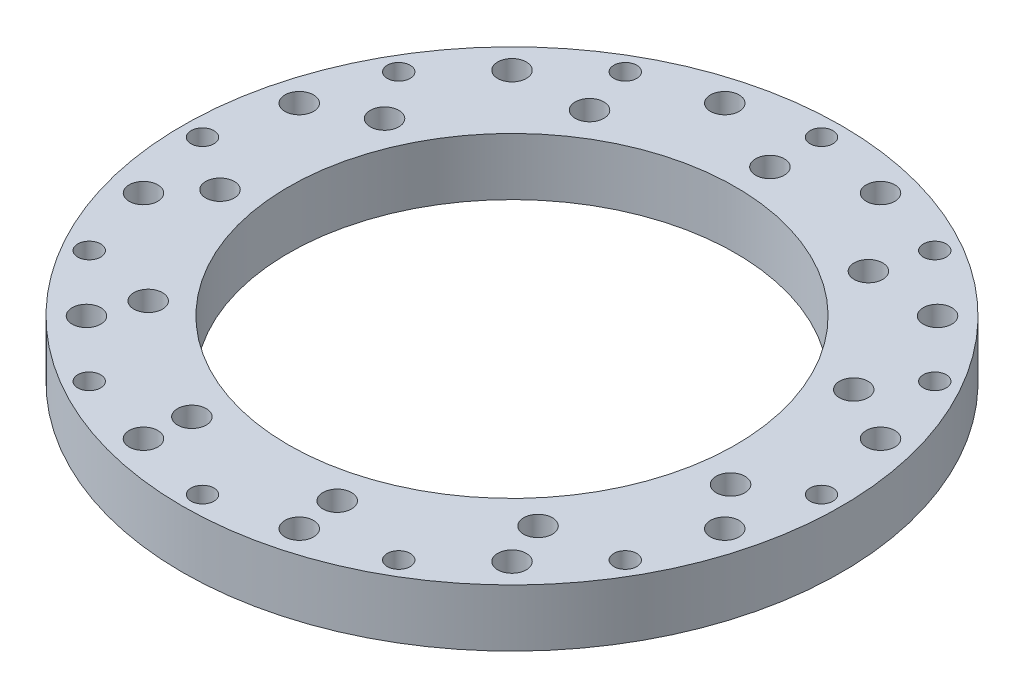
SolidWorks part; units mm, degrees
ref_plane "Front Plane" through (0, 0, 0) normal (0, 0, 1) x (1, 0, 0)
ref_plane "Top Plane" through (0, 0, 0) normal (0, 1, 0) x (1, 0, 0)
ref_plane "Right Plane" through (0, 0, 0) normal (1, 0, 0) x (0, 0, -1)
sketch "Sketch1" plane through (0, 0, 0) normal (0, 1, 0) x (1, 0, 0)
  line L0 (0, 0) -> (0, 52.5) construction
  line L1 (0, 0) -> (13.588, 50.7111) construction
  circle A12 centre (0, 0) radius 39
  circle A13 centre (0, 0) radius 57.5
  circle A14 centre (0, 0) radius 54 construction
  circle A15 centre (0, 54) radius 2
  circle A16 centre (27, 46.7654) radius 2
  circle A17 centre (46.7654, 27) radius 2
  circle A18 centre (54, 0) radius 2
  circle A19 centre (46.7654, -27) radius 2
  circle A20 centre (27, -46.7654) radius 2
  circle A21 centre (0, -54) radius 2
  circle A22 centre (-27, -46.7654) radius 2
  circle A23 centre (-46.7654, -27) radius 2
  circle A24 centre (-54, 0) radius 2
  circle A25 centre (-46.7654, 27) radius 2
  circle A26 centre (-27, 46.7654) radius 2
  circle A27 centre (0, 0) radius 52.5 construction
  circle A34 centre (13.588, 50.7111) radius 2.5
  circle A35 centre (37.1231, 37.1231) radius 2.5
  circle A36 centre (50.7111, 13.588) radius 2.5
  circle A37 centre (50.7111, -13.588) radius 2.5
  circle A38 centre (37.1231, -37.1231) radius 2.5
  circle A39 centre (13.588, -50.7111) radius 2.5
  circle A40 centre (-13.588, -50.7111) radius 2.5
  circle A41 centre (-37.1231, -37.1231) radius 2.5
  circle A42 centre (-50.7111, -13.588) radius 2.5
  circle A43 centre (-50.7111, 13.588) radius 2.5
  circle A44 centre (-37.1231, 37.1231) radius 2.5
  circle A45 centre (-13.588, 50.7111) radius 2.5
  point P21 (0, 0)
  point P28 (0, 0)
  point P56 (0, 0)
  point P60 (0, 0)
  dimension "D1" = 105
  dimension "D2" = 15
  dimension "D4" = 115
  dimension "D5" = 78
  dimension "D6" = 108
  dimension "D7" = 4
  dimension "D3" = 5
  dimension "D8" = 12
extrude "Boss-Extrude1" add sketch "Sketch1" along normal blind 10
sketch "Sketch2" plane through (0, 10, 0) normal (0, 1, 0) x (1, 0, 0)
  circle A0 centre (0, 0) radius 45 construction
  circle A1 centre (0, 45) radius 2.5
  circle A2 centre (24.3288, 37.8564) radius 2.5
  circle A3 centre (40.9334, 18.6937) radius 2.5
  circle A4 centre (44.542, -6.4042) radius 2.5
  circle A5 centre (34.0087, -29.4687) radius 2.5
  circle A6 centre (12.678, -43.1772) radius 2.5
  circle A7 centre (-12.678, -43.1772) radius 2.5
  circle A8 centre (-34.0087, -29.4687) radius 2.5
  circle A9 centre (-44.542, -6.4042) radius 2.5
  circle A10 centre (-40.9334, 18.6937) radius 2.5
  circle A11 centre (-24.3288, 37.8564) radius 2.5
  point P27 (0, 0)
  dimension "D1" = 90
  dimension "D2" = 5
extrude "Cut-Extrude1" cut sketch "Sketch2" against normal blind 10
sketch "Sketch4" plane through (0, 0, 0) normal (0, 1, 0) x (1, 0, 0)
  circle A0 centre (0, 0) radius 45 construction
  circle A1 centre (0, 45) radius 5
  circle A2 centre (0, 45) radius 2.5
  circle A3 centre (24.3288, 37.8564) radius 2.5
  circle A4 centre (40.9334, 18.6937) radius 2.5
  circle A5 centre (44.542, -6.4042) radius 2.5
  circle A6 centre (34.0087, -29.4687) radius 2.5
  circle A7 centre (12.678, -43.1772) radius 2.5
  circle A8 centre (-12.678, -43.1772) radius 2.5
  circle A9 centre (-34.0087, -29.4687) radius 2.5
  circle A10 centre (-44.542, -6.4042) radius 2.5
  circle A11 centre (-40.9334, 18.6937) radius 2.5
  circle A12 centre (-24.3288, 37.8564) radius 2.5
  circle A13 centre (24.3288, 37.8564) radius 5
  circle A14 centre (40.9334, 18.6937) radius 5
  circle A15 centre (44.542, -6.4042) radius 5
  circle A16 centre (34.0087, -29.4687) radius 5
  circle A17 centre (12.678, -43.1772) radius 5
  circle A18 centre (-12.678, -43.1772) radius 5
  circle A19 centre (-34.0087, -29.4687) radius 5
  circle A20 centre (-44.542, -6.4042) radius 5
  circle A21 centre (-40.9334, 18.6937) radius 5
  circle A22 centre (-24.3288, 37.8564) radius 5
  point P29 (0, 0)
  point P50 (0, 0)
  dimension "D1" = 10
  dimension "D2" = 11
  dimension "D3" = 11
extrude "Boss-Extrude3" add sketch "Sketch4" against normal blind 0.4
